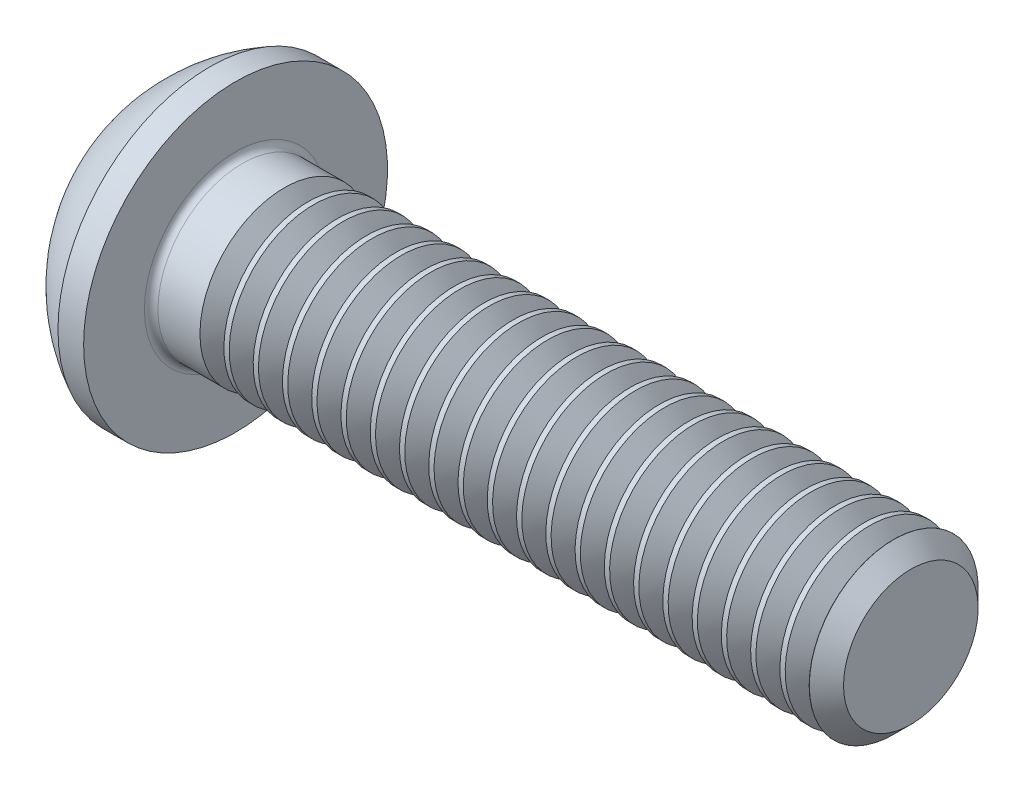
SolidWorks part; units mm, degrees
ref_plane "Plane1" through (0, 0, 0) normal (0, 0, 1) x (1, 0, 0)
ref_plane "Plane2" through (0, 0, 0) normal (0, 1, 0) x (1, 0, 0)
ref_plane "Plane3" through (0, 0, 0) normal (1, 0, 0) x (0, 0, -1)
sketch "BodySke" plane through (0, 0, 0) normal (0, 0, 1) x (1, 0, 0)
  line L0 (11.5, 0) -> (11.5, 0.9965)
  line L1 (11.2465, 1.25) -> (1.5, 1.25)
  line L2 (1.5, 1.25) -> (1.5, 2.25)
  line L3 (1.5, 2.25) -> (1.12, 2.25)
  line L4 (0, 0) -> (101.6, 0) construction
  line L5 (1.5, -2.25) -> (1.12, -2.25) construction
  line L6 (55.6768, -1.25) -> (1.5, -1.25) construction
  line L7 (11.5, 0) -> (0, 0)
  line L8 (0, 1.125) -> (0, -1.125) construction
  line L9 (0, 0) -> (0, 1.125)
  line L10 (11.5, 0.9965) -> (11.2465, 1.25)
  line L11 (11.5, -0.9965) -> (11.2465, -1.25) construction
  line L12 (1.95, 9.525) -> (1.95, -1.25) construction
  line L13 (1.5, 9.525) -> (1.5, -1.25) construction
  arc A1 (0, 1.125) -> (1.12, 2.25) centre (2.255, 0) cw
  dimension "Diameter" = 2.5
  dimension "Length" = 10
  dimension "Head_dia" = 4.5
  dimension "D1" = 2.25
  dimension "Head_ht" = 1.5
  dimension "Head_side_ht" = 0.38
  dimension "Minor_dia" = 1.993
  dimension "Body_ch_ang" = 45
  dimension "Advance" = 0.45
  dimension "Thread_nom" = 10
revolve "BaseBody" add sketch "BodySke" angle 360 about L4
cosmetic thread "ThreadCosmetic" [suppressed] parameters "Thread_length"=9.1, "Thread_minor"=1.993
fillet "Fillet1" radius 0.1 1 edges at (1.5, 0, 1.25)
sketch "Sketch2" plane through (0, 0, 0) normal (0, 0, 1) x (1, 0, 0)
  line L0 (0, 0.75) -> (0.8, 0.75)
  line L1 (0.8, 0.75) -> (1.233, 0)
  line L3 (1.233, 0) -> (0, 0)
  line L4 (0, 0) -> (0, 0.75)
  line L5 (0, -0.75) -> (0.8, -0.75) construction
  line L6 (0, 0) -> (47.625, 0) construction
  dimension "D2" = 60
  dimension "PreBroach_depth" = 0.8
  dimension "PreBroach_dia" = 1.5
revolve "PreBroach" cut sketch "Sketch2" angle 360 about L6
sketch "Sketch3" plane through (0, 0, 0) normal (1, 0, 0) x (0, 0, -1)
  line L0 (-0.75, -0.433) -> (-0.75, 0.433)
  line L1 (-0.75, 0.433) -> (0, 0.866)
  line L2 (0, 0.866) -> (0.75, 0.433)
  line L3 (0.75, 0.433) -> (0.75, -0.433)
  line L4 (0.75, -0.433) -> (0, -0.866)
  line L5 (0, -0.866) -> (-0.75, -0.433)
  dimension "Hex_size" = 1.5
  dimension "D3" = 1.5
  dimension "D1" = 0.75
  dimension "D2" = 0.75
extrude "Hex" cut sketch "Sketch3" along normal blind 0.8
sketch "ThdSchSke" plane through (0, 0, 0) normal (0, 0, 1) x (1, 0, 0)
  line L0 (2.4, -0.9965) -> (2.2225, -1.25)
  line L1 (2.4, -0.9965) -> (2.5775, -1.25)
  line L2 (2.5775, -1.25) -> (2.5775, -1.5625)
  line L3 (-3.175, 0) -> (5.1513, 0) construction
  line L5 (2.5775, -1.5625) -> (2.2225, -1.5625)
  line L6 (2.2225, -1.5625) -> (2.2225, -1.25)
  dimension "Diameter" = 2.5
  dimension "Thread_minor" = 1.993
  dimension "SideAngle" = 55
  dimension "VeeAngle" = 70
  dimension "Overcut" = 3.125
  dimension "Start" = 2.4
revolve "ThreadSchematic" cut sketch "ThdSchSke" angle 360 about L3
pattern_linear "ThdSchPat" count 21 spacing 0.4333 along (1, 0, 0) of "ThreadSchematic"
equation "\"D1@BodySke\" = \"Head_dia@BodySke\" * .5"
equation "\"Thread_minor@ThreadCosmetic\" = \"Minor_dia@BodySke\""
equation "\"D1@Sketch3\" = \"Hex_size@Sketch3\" / 2"
equation "\"D2@Sketch3\" = \"D1@Sketch3\""
equation "\"D3@Sketch3\" = \"Hex_size@Sketch3\""
equation "\"Thread_length@ThreadCosmetic\" = ((sgn( (\"Length@BodySke\" - \"Advance@BodySke\" * 2.0) - \"Thread_nom@BodySke\" )-1)*( (\"Length@BodySke\" - \"Advance@BodySke\" * 2.0) - \"Thread_nom@BodySke\" ))/-2+ \"Thread_nom@BodySke\""
equation "\"Thread_minor@ThdSchSke\" = \"Minor_dia@BodySke\""
equation "\"Diameter@ThdSchSke\" = \"Diameter@BodySke\""
equation "\"Overcut@ThdSchSke\" = \"Diameter@BodySke\" * 1.25"
equation "\"Start@ThdSchSke\" = \"Head_ht@BodySke\" + \"Length@BodySke\" - \"Thread_length@ThreadCosmetic\"  '---Non-countersunk---"
equation "\"Num_threads@ThdSchPat\" = int( \"Thread_length@ThreadCosmetic\" / \"Advance@BodySke\" + 0.999 )  + 1"
equation "\"Advance@ThdSchPat\" = \"Thread_length@ThreadCosmetic\" /  (\"Num_threads@ThdSchPat\" - 1) 'relax it"
equation "\"Num_threads@ThdSchPat\" = \"Num_threads@ThdSchPat\" - sgn( \"Num_threads@ThdSchPat\" - 1) '---chamfered tips only---"
